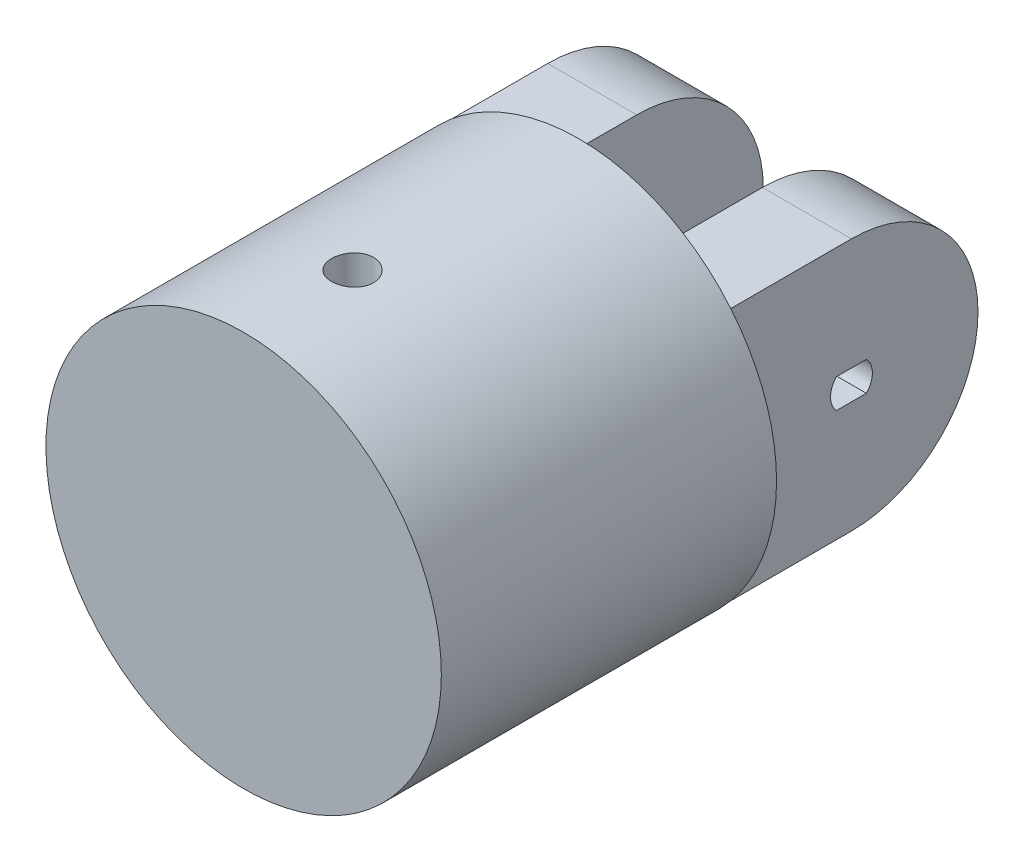
SolidWorks part; units mm, degrees
ref_plane "Plano frontal" through (0, 0, 0) normal (0, 0, 1) x (1, 0, 0)
ref_plane "Plano superior" through (0, 0, 0) normal (0, 1, 0) x (1, 0, 0)
ref_plane "Plano direito" through (0, 0, 0) normal (1, 0, 0) x (0, 0, -1)
sketch "Esboço1" plane through (0, 0, 0) normal (0, 0, 1) x (1, 0, 0)
  circle A0 centre (0, 0) radius 23.59
extrude "Ressalto-extrusão1" add sketch "Esboço1" against normal blind 30 and the other way blind 10
sketch "Esboço2" plane through (0, 0, -30) normal (0, 0, -1) x (-1, 0, 0)
  line L0 (-23.59, 0) -> (23.59, 0) construction
  line L1 (0, 0) -> (-7.5, 0)
  line L2 (0, 0) -> (7.5, 0)
  line L3 (7.5, 0) -> (7.5, 15.1011)
  line L4 (7.5, 15.1011) -> (18.123, 15.1011)
  line L5 (18.123, 15.1011) -> (18.123, -15.1011)
  line L6 (18.123, -15.1011) -> (7.5, -15.1011)
  line L7 (7.5, -15.1011) -> (7.5, 0)
  line L8 (0, 15.1011) -> (0, -15.1011) construction
  line L9 (-7.5, -15.1011) -> (-7.5, 0)
  line L10 (-18.123, -15.1011) -> (-7.5, -15.1011)
  line L11 (-18.123, 15.1011) -> (-18.123, -15.1011)
  line L12 (-7.5, 15.1011) -> (-18.123, 15.1011)
  line L13 (-7.5, 0) -> (-7.5, 15.1011)
  circle A0 centre (0, 0) radius 23.59 construction
  point P7 (0, 0)
  point P18 (0, 0)
extrude "Ressalto-extrusão2" add sketch "Esboço2" along normal blind 30 contours L9 L13 L12 L11 L10 | L7 L6 L5 L4 L3
sketch "Esboço3" plane through (-18.123, 0, 0) normal (-1, 0, 0) x (0, 0, 1)
  line L0 (-54.8897, 10.8681) -> (-54.4114, 10.4719) construction
  line L1 (-44.405, -15.1011) -> (-60, -15.1011) construction
  line L2 (-55.3425, -10.4122) -> (-55.2628, -10.3319) construction
  line L4 (-44.405, 18.1724) -> (-62.563, 18.1724)
  line L5 (-62.563, 18.1724) -> (-62.563, -18.2519)
  line L6 (-62.563, -18.2519) -> (-44.405, -18.2519)
  line L7 (-44.405, -18.2519) -> (-44.405, -15.1011)
  line L9 (-44.405, 18.1724) -> (-44.405, 15.1011)
  line L10 (-60, 15.1011) -> (-30, 15.1011) construction
  arc A1 (-44.405, 15.1011) -> (-44.405, -15.1011) centre (-44.405, 0) ccw
extrude "Corte-extrusão1" cut sketch "Esboço3" against normal mid plane 118.81
sketch "Esboço4" plane through (-18.123, 0, 0) normal (-1, 0, 0) x (0, 0, 1)
  line L0 (-46.1904, 1.75) -> (-42.6196, 1.75)
  line L4 (-46.1904, -1.75) -> (-42.6196, -1.75)
  arc A1 (-46.1904, 1.75) -> (-46.1904, -1.75) centre (-44.405, 0) ccw
  arc A2 (-42.6196, -1.75) -> (-42.6196, 1.75) centre (-44.405, 0) ccw
  dimension "D1" = 5
  dimension "D2" = 1.75
  dimension "D3" = 1.75
extrude "Corte-extrusão2" cut sketch "Esboço4" against normal mid plane 158.81
ref_plane "Plane1" through (0, 23.59, 0) normal (0, 1, 0) x (1, 0, 0)
sketch "Sketch2" plane through (0, 23.59, 0) normal (0, 1, 0) x (1, 0, 0)
  line L0 (-23.59, -10) -> (23.59, -10) construction
  circle A0 centre (0, 2.99) radius 2.5
  dimension "D1" = 12.99
extrude "Cut-Extrude1" cut sketch "Sketch2" against normal through all
